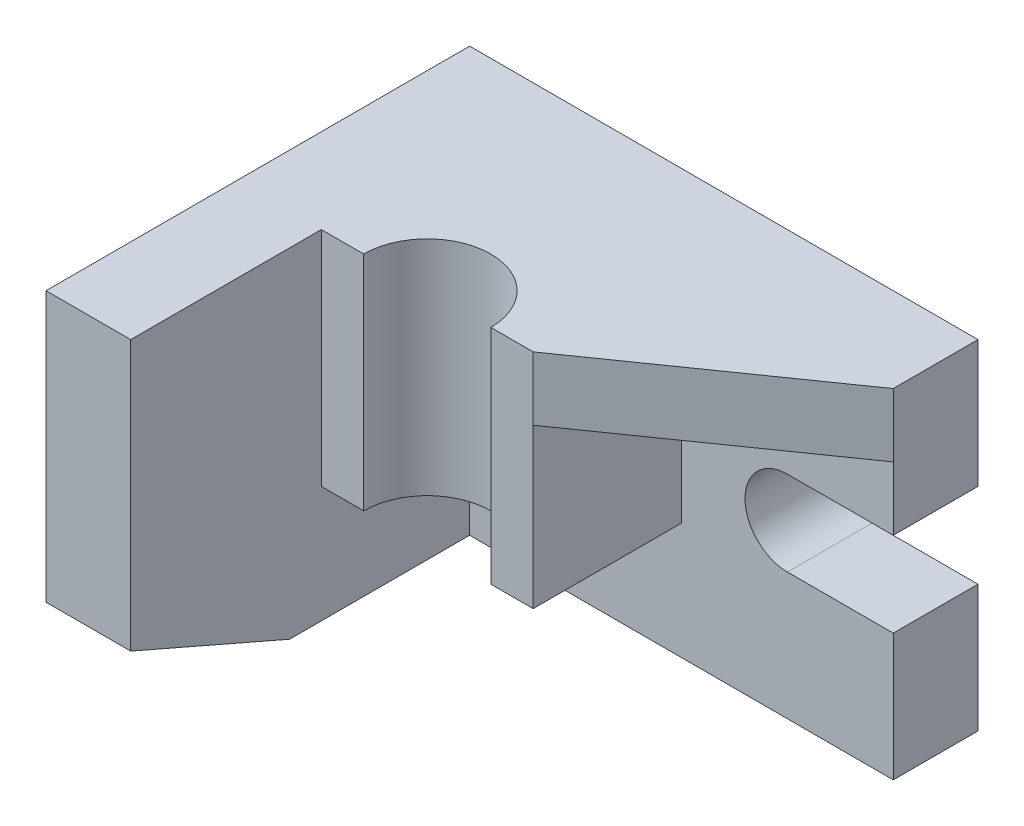
SolidWorks part; units mm, degrees
ref_plane "Front Plane" through (0, 0, 0) normal (0, 0, 1) x (1, 0, 0)
ref_plane "Top Plane" through (0, 0, 0) normal (0, 1, 0) x (1, 0, 0)
ref_plane "Right Plane" through (0, 0, 0) normal (1, 0, 0) x (0, 0, -1)
sketch "Sketch1" plane through (0, 0, 0) normal (0, 0, 1) x (1, 0, 0)
  line L1 (-48, -32) -> (48, -32)
  line L2 (-48, -32) -> (-48, 32)
  line L3 (-48, 32) -> (48, 32)
  line L4 (48, -32) -> (48, 32)
  line L5 (-48, -32) -> (48, 32) construction
  line L6 (-48, 32) -> (48, -32) construction
  point P0 (0, 0)
  dimension "D1" = 96
  dimension "D2" = 64
extrude "Boss-Extrude1" add sketch "Sketch1" against normal blind 16
sketch "Sketch2" plane through (-48, 0, 0) normal (-1, 0, 0) x (0, 0, 1)
  line L0 (0, 32) -> (64, 32)
  line L1 (64, 32) -> (64, -18.9463)
  line L2 (64, -18.9463) -> (34, -32)
  line L3 (34, -32) -> (0, -32)
  line L4 (0, -32) -> (0, 32)
  dimension "D1" = 34
  dimension "D2" = 30
extrude "Boss-Extrude2" add sketch "Sketch2" against normal blind 16
sketch "Sketch3" plane through (0, 32, 0) normal (0, 1, 0) x (1, 0, 0)
  line L1 (-32, 0) -> (8, 0)
  line L2 (-32, 0) -> (-32, -28)
  line L3 (-32, -28) -> (8, -28)
  line L4 (8, 0) -> (8, -28)
  dimension "D1" = 40
  dimension "D2" = 28
extrude "Boss-Extrude3" add sketch "Sketch3" against normal blind 42
sketch "Sketch4" plane through (0, 32, 0) normal (0, 1, 0) x (1, 0, 0)
  line L0 (8, -28) -> (48, 0)
  line L1 (48, 0) -> (8, 0)
  line L2 (8, 0) -> (8, -28)
extrude "Boss-Extrude4" add sketch "Sketch4" against normal blind 12
sketch "Sketch5" plane through (0, 0, 0) normal (0, 0, 1) x (1, 0, 0)
  line L0 (48, 8) -> (28, 8)
  line L1 (48, -32) -> (48, 20) construction
  line L2 (48, -8) -> (28, -8)
  arc A1 (28, 8) -> (28, -8) centre (28, 0) ccw
  line M2 (48, -32) -> (48, 20)
  dimension "D1" = 16
  dimension "D2" = 40
  dimension "D3" = 20
  dimension "D4" = 20
extrude "Cut-Extrude1" cut sketch "Sketch5" against normal through all and the other way through all contours L0 A1 L2 M2
sketch "Sketch6" plane through (0, 32, 0) normal (0, 1, 0) x (1, 0, 0)
  line L0 (-32, -28) -> (8, -28) construction
  circle A0 centre (-12, -28) radius 12
  dimension "D1" = 24
extrude "Cut-Extrude2" cut sketch "Sketch6" against normal through all
